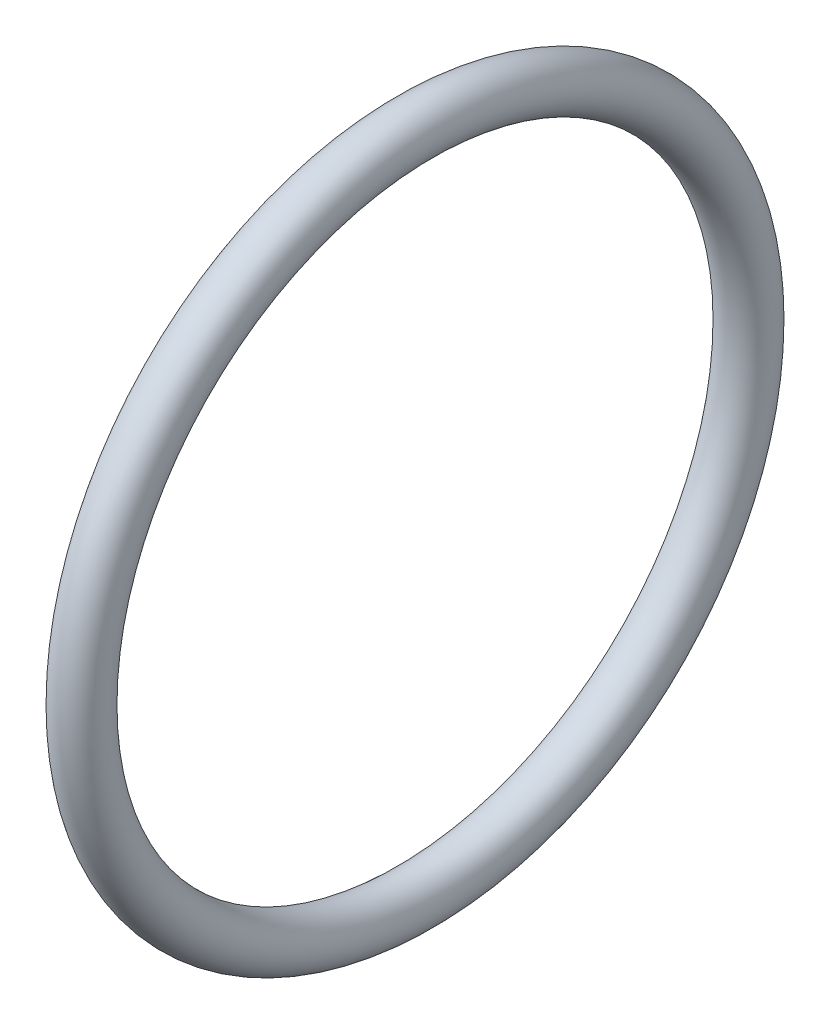
SolidWorks part; units mm, degrees
ref_plane "Front Plane" through (0, 0, 0) normal (0, 0, 1) x (1, 0, 0)
ref_plane "Top Plane" through (0, 0, 0) normal (0, 1, 0) x (1, 0, 0)
ref_plane "Right Plane" through (0, 0, 0) normal (1, 0, 0) x (0, 0, -1)
sketch "Sketch1" plane through (0, 0, 0) normal (0, 0, 1) x (1, 0, 0)
  line L0 (0, 0) -> (14.7628, 0) construction
  line L1 (0, 25) -> (5.5547, 25) construction
  circle A0 centre (0, 23.25) radius 1.75
  dimension "D2" = 3.5
  dimension "D1" = 25
revolve "Revolve1" add sketch "Sketch1" angle 360 about L0
sketch "Sketch2" plane through (0, 0, 0) normal (1, 0, 0) x (0, 0, -1)
  circle A0 centre (0, 0) radius 22.5618 construction
